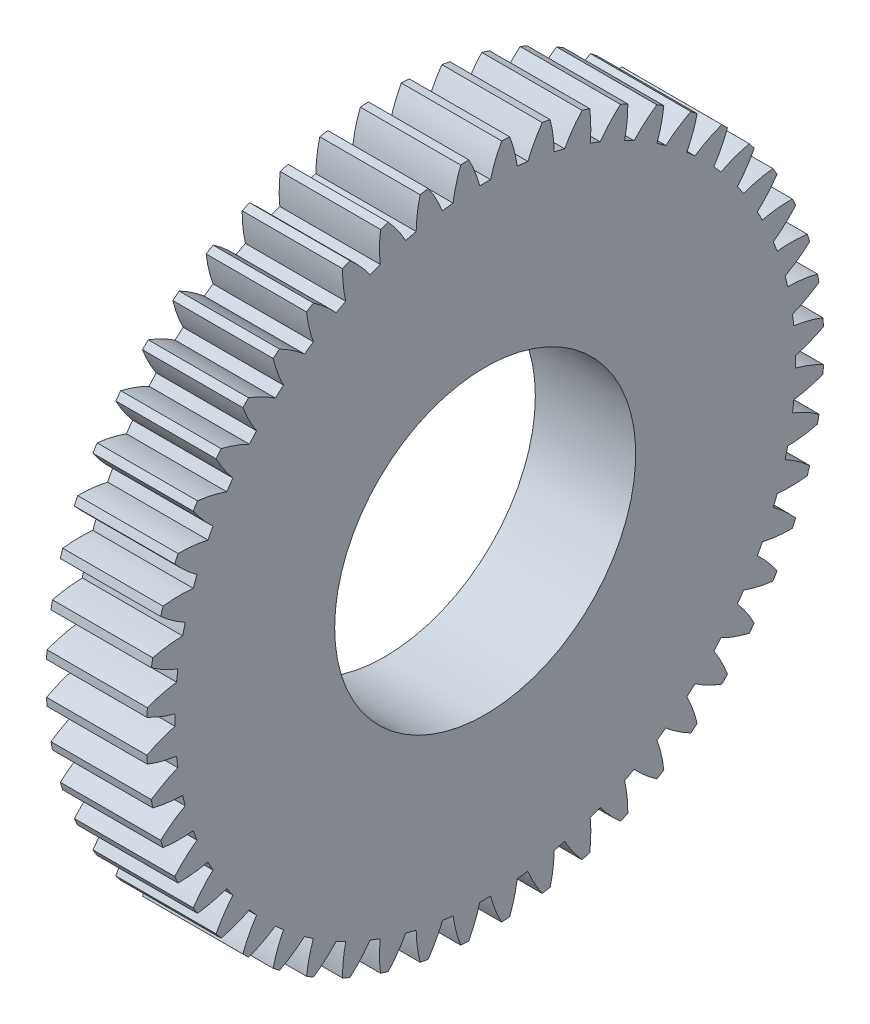
SolidWorks part; units mm, degrees
ref_plane "Plane1" through (0, 0, 0) normal (0, 0, 1) x (1, 0, 0)
ref_plane "Plane2" through (0, 0, 0) normal (0, 1, 0) x (1, 0, 0)
ref_plane "Plane3" through (0, 0, 0) normal (1, 0, 0) x (0, 0, -1)
other "Configuration Table"
sketch "HoldingSke" plane through (0, 0, 0) normal (0, 1, 0) x (1, 0, 0)
  line L0 (0, 0) -> (500.4096, -640.4951)
  line L1 (-15, 0) -> (100, 0) construction
  line L2 (0, 0) -> (-2.1039, 2.3779)
  line L3 (0, 0) -> (-11.863, 4.5341)
  line L4 (0, 0) -> (5.3169, 6.8053)
  line L5 (0, 0) -> (-47.5972, -17.7524)
  line L6 (0, 0) -> (-4.2111, -2.8413)
  line L7 (-2.1039, 2.3779) -> (8.8308, 51.9871)
  line L8 (-76.2, 54.61) -> (-75.184, 54.61)
  line L9 (-71.009, 38.7566) -> (-53.1078, 45.2721)
  line L10 (-76.2, 71.12) -> (104.1128, 71.12)
  line L11 (0, 0) -> (-5.08, 0)
  line L12 (-76.2, 101.6) -> (-76.1716, 101.6)
  line L13 (24.9733, 27.94) -> (52.9518, 28.4284)
  line L14 (24.9733, 27.94) -> (25.0241, 27.9398)
  line L15 (24.9733, 27.94) -> (100.4021, 29.52)
  circle A0 centre (0, 0) radius 0.3969
  circle A1 centre (0, 0) radius 19.6342
  circle A2 centre (0, 0) radius 38.1
  circle A3 centre (0, 0) radius 0.3969
  dimension "MHD" = 39.2684
  dimension "Hub_dia" = 76.2
  dimension "Bore" = 0.7937
  dimension "MBD" = 0.7937
  dimension "Num_teeth" = 52
  dimension "Pitch" = 812.8
  dimension "Overall_len" = 50.8
  dimension "Show_teeth" = 52
  dimension "Thickness" = 5.08
  dimension "OAL" = 50.8001
  dimension "T_dim" = 1.016
  dimension "Ap" = 20
  dimension "H" = 19.05
  dimension "Pitch_radius" = 180.3128
  dimension "Width" = 5.08
  dimension "Backlash" = 0.0284
  dimension "Addendum_fac" = 1
  dimension "Dedendum_fac" = 1.2
  dimension "Clearance_fac" = 0.2
  dimension "Dedendum_add" = 0.0508
sketch "BasProSke" plane through (0, 0, 0) normal (0, 1, 0) x (1, 0, 0)
  line L0 (-10, 0) -> (60, 0) construction
  line L1 (0, 0) -> (0, 21.4312)
  line L2 (0, 0) -> (6.35, 0)
  line L3 (6.35, 0) -> (6.35, 21.4312)
  line L4 (6.35, 21.4312) -> (0, 21.4312)
  dimension "Thickness" = 6.35
  dimension "Diameter" = 42.8625
revolve "Base-Revolve" add sketch "BasProSke" angle 360 about L0
sketch "TooCutSke" plane through (0, 0, 0) normal (1, 0, 0) x (0, 0, -1)
  line L1 (0, 0) -> (0, 107) construction
  line L2 (0, 0) -> (-0.6731, 20.6265) construction
  line L3 (0, 0) -> (-2.4912, 41.1838) construction
  line L4 (-0.6731, 20.6265) -> (-1.2456, 20.5919) construction
  arc A0 (0.3404, 19.6312) -> (-0.3404, 19.6312) centre (0, 0) ccw
  arc A1 (1.0518, 21.4309) -> (-1.0518, 21.4309) centre (0, 0) ccw
  circle A2 centre (0, 0) radius 20.6375 construction
  circle A3 centre (0, 0) radius 19.3929 construction
  arc A4 (-0.3404, 19.6312) -> (-1.0518, 21.4309) centre (-8.3202, 17.5174) ccw
  arc A5 (1.0518, 21.4309) -> (0.3404, 19.6312) centre (8.3202, 17.5174) ccw
  dimension "Root_dia" = 39.2684
  dimension "Overcut_dia" = 42.9133
  dimension "Pitch_dia" = 41.275
  dimension "Base_dia" = 38.7858
  dimension "Flank_rad" = 8.255
  dimension "Half_ang" = 3.462
  dimension "Half_CT" = 0.5735
extrude "ToothCut" cut sketch "TooCutSke" along normal through all
fillet "Breaks" [suppressed] radius 0.0159
fillet "RootFillets" [suppressed] radius 0.2095
pattern_circular "TeethCuts" count 52 every 6.923 about axis through (-10, 0, 0) along (1, 0, 0) of "ToothCut", "RootFillets", "Breaks"
sketch "HubNeaOneSke" plane through (0, 0, 0) normal (-1, 0, 0) x (0, 0, 1)
  circle A0 centre (0, 0) radius 19.6342
  dimension "Diameter" = 39.2684
extrude "HubNearOne" [suppressed] add sketch "HubNeaOneSke" along normal blind 44.4501
sketch "HubNeaBotSke" plane through (0, 0, 0) normal (-1, 0, 0) x (0, 0, 1)
  circle A0 centre (0, 0) radius 19.6342
  dimension "Diameter" = 39.2684
extrude "HubNearBoth" [suppressed] add sketch "HubNeaBotSke" along normal blind 22.225
ref_plane "FarPln" through (6.35, 0, 0) normal (1, 0, 0) x (0, 0, -1)
sketch "HubFarSke" plane through (6.35, 0, 0) normal (1, 0, 0) x (0, 0, -1)
  circle A0 centre (0, 0) radius 19.6342
  dimension "Diameter" = 39.2684
extrude "HubFar" [suppressed] add sketch "HubFarSke" along normal blind 22.225
sketch "BorSke" plane through (0, 0, 0) normal (1, 0, 0) x (0, 0, -1)
  circle A0 centre (0, 0) radius 9.525
  dimension "D1" = 19.05
extrude "Bore" cut sketch "BorSke" along normal mid plane 101.6001
sketch "KeySke" plane through (0, 0, 0) normal (1, 0, 0) x (0, 0, -1)
  line L0 (-0.127, 0) -> (-0.127, 0.6191)
  line L1 (-0.127, 0.6191) -> (0.127, 0.6191)
  line L2 (0.127, 0.6191) -> (0.127, 0)
  line L3 (0, 0) -> (0, 34) construction
  line L4 (-0.127, 0) -> (0.127, 0)
  dimension "Offset" = 0.6191
  dimension "Width" = 0.254
extrude "Keyway" [suppressed] cut sketch "KeySke" along normal mid plane 101.6001
pattern_circular "Keyway2" [suppressed] count 2 every 90 about axis through (-10, 0, 0) along (1, 0, 0)
equation "' \"Pitch@HoldingSke\" = 4"
equation "' \"Num_teeth@HoldingSke\" = 12"
equation "' \"Ap@HoldingSke\" =  20"
equation "' \"Ap@HoldingSke\" = 20"
equation "' \"Width@HoldingSke\" = 0.5"
equation "' \"Hub_dia@HoldingSke\"= 1"
equation "' \"Hub_dia@HoldingSke\" = 1"
equation "' \"Overall_len@HoldingSke\" = 1.0"
equation "' \"Bore@HoldingSke\" = 0.75"
equation "' \"T_dim@HoldingSke\" = 0.85"
equation "' \"Width@KeySke\" = 0.25"
equation "' \"Show_teeth@HoldingSke\" = 13"
equation "' \"Backlash@HoldingSke\" = 0.009"
equation "' \"Addendum_fac@HoldingSke\" = 1.0"
equation "' \"Dedendum_fac@HoldingSke\" = 1.25"
equation "' \"Dedendum_add@HoldingSke\" = 0.00005"
equation "' \"Clearance_fac@HoldingSke\" = 0.25"
equation "' \"Pitch@HoldingSke\" = 0.5"
equation "' \"Num_teeth@HoldingSke\" = 23"
equation "' \"Show_teeth@HoldingSke\" = 23"
equation "' \"Backlash@HoldingSke\" = 0.0375"
equation "\"Overcut_dia@TooCutSke\" = (\"Num_teeth@HoldingSke\" + 2 * \"Addendum_fac@HoldingSke\") / \"Pitch@HoldingSke\" + 0.002"
equation "\"Pitch_dia@TooCutSke\" = \"Num_teeth@HoldingSke\" / \"Pitch@HoldingSke\""
equation "\"Base_dia@TooCutSke\" = \"Num_teeth@HoldingSke\" / \"Pitch@HoldingSke\" * cos((\"Ap@HoldingSke\"  * 3.14159265 / 180))"
equation "\"Root_dia@TooCutSke\" = (\"Num_teeth@HoldingSke\" + 2) / \"Pitch@HoldingSke\" - 2 * (\"Addendum_fac@HoldingSke\" + \"Dedendum_fac@HoldingSke\") / \"Pitch@HoldingSke\" - \"Dedendum_add@HoldingSke\" * 2"
equation "\"Half_ang@TooCutSke\" = 180 / \"Num_teeth@HoldingSke\""
equation "\"Half_CT@TooCutSke\" = \"Num_teeth@HoldingSke\" / \"Pitch@HoldingSke\" * sin((3.14159265 / 2 / \"Num_teeth@HoldingSke\")) / 2 - 7 * \"Backlash@HoldingSke\" / 4"
equation "\"Flank_rad@TooCutSke\" = \"Num_teeth@HoldingSke\" / \"Pitch@HoldingSke\" / 5"
equation "\"Radius@RootFillets\" = \"Clearance_fac@HoldingSke\" / \"Pitch@HoldingSke\" + \"Dedendum_add@HoldingSke\""
equation "\"Break_rad@Breaks\" = 0.02 / \"Pitch@HoldingSke\""
equation "\"Thickness@HoldingSke\" = \"Width@HoldingSke\""
equation "\"OAL@HoldingSke\" = \"Thickness@HoldingSke\""
equation "\"MHD@HoldingSke\" = (\"Num_teeth@HoldingSke\" + 2) / \"Pitch@HoldingSke\" - 2 * (\"Addendum_fac@HoldingSke\" + \"Dedendum_fac@HoldingSke\")  / \"Pitch@HoldingSke\" - \"Dedendum_add@HoldingSke\" * 2"
equation "\"MBD@HoldingSke\" = (\"Num_teeth@HoldingSke\" + 2) / \"Pitch@HoldingSke\" - 2 * (\"Addendum_fac@HoldingSke\" + \"Dedendum_fac@HoldingSke\")  / \"Pitch@HoldingSke\" - \"Dedendum_add@HoldingSke\" * 2 - 0.002"
equation "\"MHD@HoldingSke\" = ((sgn( \"MHD@HoldingSke\" - \"Hub_dia@HoldingSke\" )-1)*( \"MHD@HoldingSke\" - \"Hub_dia@HoldingSke\" ))/-2+ \"Hub_dia@HoldingSke\""
equation "\"MBD@HoldingSke\" = ((sgn( \"MBD@HoldingSke\" - \"Bore@HoldingSke\" )-1)*( \"MBD@HoldingSke\" - \"Bore@HoldingSke\" ))/-2+ \"Bore@HoldingSke\""
equation "\"OAL@HoldingSke\" = ((sgn( \"OAL@HoldingSke\" - \"Overall_len@HoldingSke\" )+1)*( \"OAL@HoldingSke\" - \"Overall_len@HoldingSke\" ))/2 + \"Overall_len@HoldingSke\" + 0.000002"
equation "\"Num_teeth@TeethCuts\" = int( \"Show_teeth@HoldingSke\" ) + 1"
equation "\"Num_teeth@TeethCuts\" = ((sgn( \"Num_teeth@TeethCuts\" - \"Num_teeth@HoldingSke\" )-1)*( \"Num_teeth@TeethCuts\" - \"Num_teeth@HoldingSke\" ))/-2+ \"Num_teeth@HoldingSke\""
equation "\"Num_teeth@TeethCuts\" = ((sgn( \"Num_teeth@TeethCuts\" - 2.0)+1)*( \"Num_teeth@TeethCuts\" - 2.0))/2 +2.0"
equation "\"Angle@TeethCuts\" = 360.0 / \"Num_teeth@HoldingSke\""
equation "\"Diameter@BasProSke\" = (\"Num_teeth@HoldingSke\" + 2 * \"Addendum_fac@HoldingSke\") / \"Pitch@HoldingSke\""
equation "\"Thickness@BasProSke\"=0.25"
equation "' \"Fillet_rad@BasProSke\" =  \"Thickness@HoldingSke\" * 0.05"
equation "' \"Fillet_rad@BasProSke\" = \"Thickness@HoldingSke\" * 0.05"
equation "\"MHD@HoldingSke\" = ((sgn( \"MHD@HoldingSke\" - \"Root_dia@TooCutSke\" )-1)*( \"MHD@HoldingSke\" - \"Root_dia@TooCutSke\" ))/-2+ \"Root_dia@TooCutSke\""
equation "\"Diameter@HubNeaOneSke\" = \"MHD@HoldingSke\""
equation "\"Length@HubNearOne\" = \"OAL@HoldingSke\" - \"Thickness@BasProSke\""
equation "\"Diameter@HubNeaBotSke\" = \"MHD@HoldingSke\""
equation "\"Length@HubNearBoth\" = ( \"OAL@HoldingSke\" - \"Thickness@BasProSke\" ) / 2.0"
equation "\"Thickness@FarPln\" = \"Thickness@BasProSke\""
equation "\"Diameter@HubFarSke\" = \"MHD@HoldingSke\""
equation "\"Length@HubFar\" = ( \"OAL@HoldingSke\" - \"Thickness@BasProSke\" ) / 2.0"
equation "\"D1@Bore\" = \"OAL@HoldingSke\" * 2.0"
equation "\"D1@Keyway\" = \"OAL@HoldingSke\" * 2.0"
equation "\"Offset@KeySke\" = \"T_dim@HoldingSke\" - \"MBD@HoldingSke\" / 2.0"
